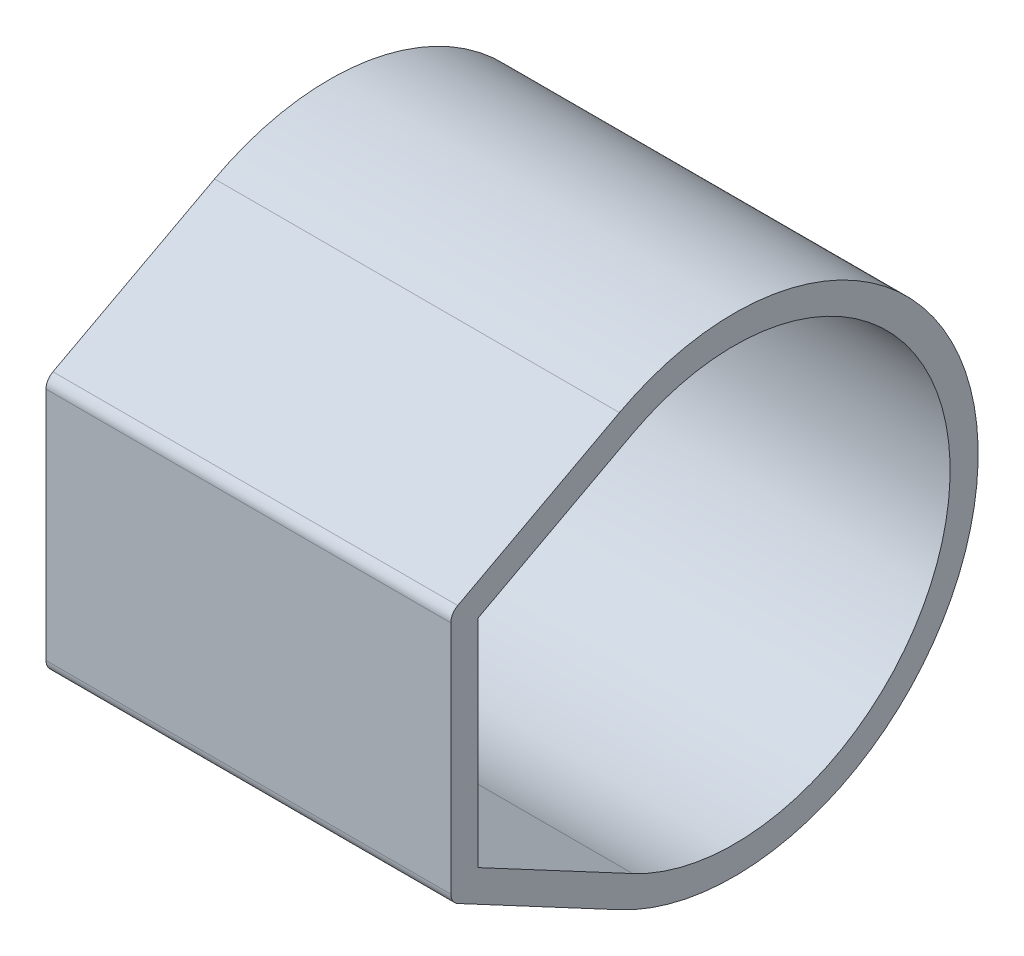
SolidWorks part; units mm, degrees
ref_plane "Front Plane" through (0, 0, 0) normal (0, 0, 1) x (1, 0, 0)
ref_plane "Top Plane" through (0, 0, 0) normal (0, 1, 0) x (1, 0, 0)
ref_plane "Right Plane" through (0, 0, 0) normal (1, 0, 0) x (0, 0, -1)
ref_plane "Plane1" through (-154.0071, 0, 0) normal (-1, 0, 0) x (0, -1, 0)
sketch "Sketch1" plane through (-154.0071, 0, 0) normal (-1, 0, 0) x (0, -1, 0)
  line L0 (-672.1698, -374.0325) -> (-669.1109, -368.2972)
  line L1 (-669.1109, -368.2972) -> (-661.1109, -368.2972)
  line L2 (-661.1109, -368.2972) -> (-658.0521, -374.0325)
  line L3 (-657.1354, -373.5435) -> (-660.3297, -367.5541)
  line L4 (-660.7579, -367.2972) -> (-669.464, -367.2972)
  line L5 (-669.8921, -367.5541) -> (-673.0865, -373.5435)
  line L6 (-658.0521, -374.0325) -> (-672.1698, -374.0325) construction
  line L7 (-657.1354, -373.5435) -> (-673.0865, -373.5435) construction
  line L8 (-665.1109, -377.7972) -> (-665.1109, -358.7972) construction
  arc A0 (-658.0521, -374.0325) -> (-672.1698, -374.0325) centre (-665.1109, -377.7972) cw
  arc A1 (-673.0865, -373.5435) -> (-657.1354, -373.5435) centre (-665.1109, -377.7972) ccw
  arc A2 (-660.3297, -367.5541) -> (-660.7579, -367.2972) centre (-660.7579, -367.7825) ccw
  arc A3 (-669.464, -367.2972) -> (-669.8921, -367.5541) centre (-669.464, -367.7825) ccw
  point P13 (-665.1109, -368.2972)
  point P15 (-665.1109, -367.2972)
  point P16 (0, 0)
  point P17 (0, 0)
  point P18 (-659.0547, -367.4548)
  point P19 (-659.9813, -368.2972)
  point P20 (0, 0)
  point P21 (0, 0)
  point P22 (0, 0)
  dimension "D1" = 1
  dimension "D2" = 1.039
  dimension "D4" = 8
  dimension "D5" = 8
  dimension "D3" = 9.5
extrude "Boss-Extrude1" add sketch "Sketch1" against normal blind 15
